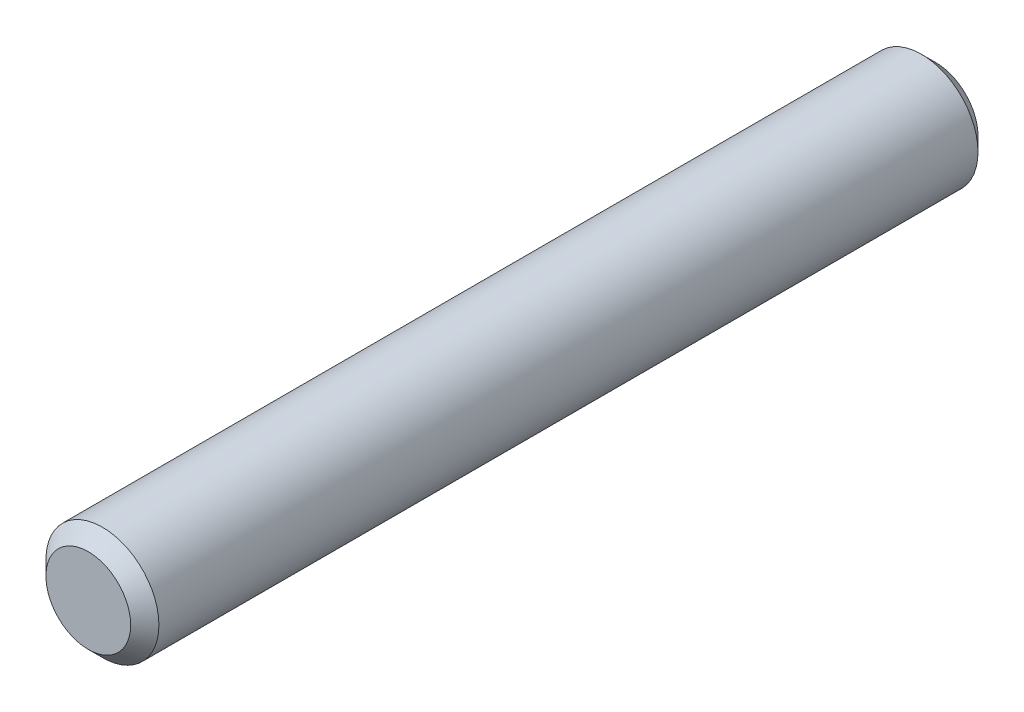
SolidWorks part; units mm, degrees
ref_plane "Front Plane" through (0, 0, 0) normal (0, 0, 1) x (1, 0, 0)
ref_plane "Top Plane" through (0, 0, 0) normal (0, 1, 0) x (1, 0, 0)
ref_plane "Right Plane" through (0, 0, 0) normal (1, 0, 0) x (0, 0, -1)
sketch "Sketch1" plane through (0, 0, 0) normal (0, 0, 1) x (1, 0, 0)
  circle A0 centre (0, 0) radius 2
  dimension "D1" = 4
extrude "Boss-Extrude1" add sketch "Sketch1" along normal mid plane 30
chamfer "Chamfer1" distance 0.5 angle 45 2 edges at (2, 0, 15) (2, 0, -15)
